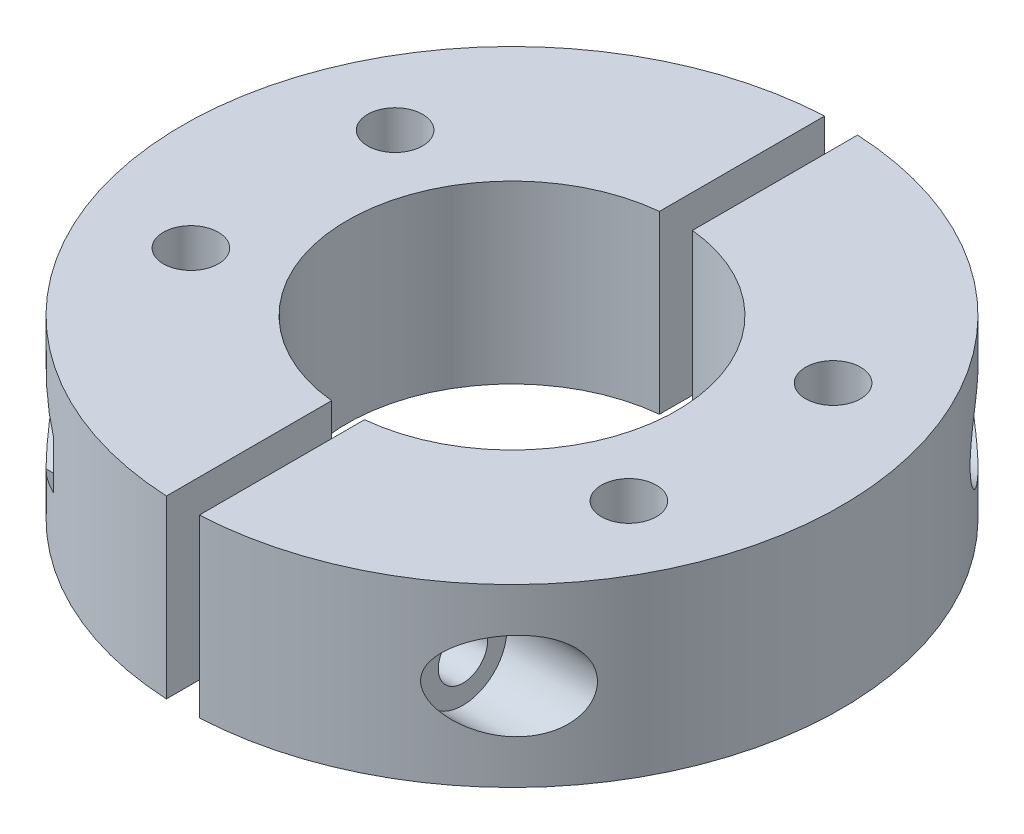
SolidWorks part; units mm, degrees
material "3D printed plastic"
ref_plane "Front Plane" through (0, 0, 0) normal (0, 0, 1) x (1, 0, 0)
ref_plane "Top Plane" through (0, 0, 0) normal (0, 1, 0) x (1, 0, 0)
ref_plane "Right Plane" through (0, 0, 0) normal (1, 0, 0) x (0, 0, -1)
sketch "Sketch1" plane through (0, 0, 0) normal (0, 1, 0) x (1, 0, 0)
  line L0 (-1.5, 29.9625) -> (-1.5, 14.9248)
  line L1 (1.5, -29.9625) -> (1.5, -14.9248)
  line L2 (1.5, 14.9248) -> (1.5, 29.9625)
  line L3 (-1.5, -14.9248) -> (-1.5, -29.9625)
  arc A0 (-1.5, 14.9248) -> (-1.5, -14.9248) centre (0, 0) ccw
  arc A1 (-1.5, 29.9625) -> (-1.5, -29.9625) centre (0, 0) ccw
  arc A2 (1.5, -14.9248) -> (1.5, 14.9248) centre (0, 0) ccw
  arc A3 (1.5, -29.9625) -> (1.5, 29.9625) centre (0, 0) ccw
  dimension "D1" = 30
  dimension "D2" = 60
  dimension "D3" = 3
extrude "Boss-Extrude1" add sketch "Sketch1" along normal blind 16
sketch "Sketch2" plane through (0, 0, 0) normal (1, 0, 0) x (0, 0, -1)
  line L0 (20.9625, 8) -> (29.9625, 8) construction
  line L1 (29.9625, 16) -> (29.9625, 0) construction
  line L2 (-29.9625, 8) -> (-20.9625, 8) construction
  line L3 (-29.9625, 16) -> (-29.9625, 0) construction
  circle A0 centre (-20.9625, 8) radius 2.25
  circle A1 centre (20.9625, 8) radius 2.25
  dimension "D1" = 4.5
  dimension "D2" = 9
extrude "Cut-Extrude1" cut sketch "Sketch2" against normal through all both and the other way through all
sketch "Sketch3" plane through (1.5, 0, 0) normal (-1, 0, 0) x (0, 0, 1)
  circle A0 centre (-20.9625, 8) radius 4
  circle A1 centre (20.9625, 8) radius 4
  dimension "D1" = 8
extrude "Cut-Extrude2" cut sketch "Sketch3" against normal through all from offset 15 offset against normal yes
sketch "Sketch4" plane through (-1.5, 0, 0) normal (1, 0, 0) x (0, 0, -1)
  line L1 (-20.9625, 12.3301) -> (-24.7125, 10.1651)
  line L2 (-24.7125, 10.1651) -> (-24.7125, 5.8349)
  line L3 (-24.7125, 5.8349) -> (-20.9625, 3.6699)
  line L4 (-20.9625, 3.6699) -> (-17.2125, 5.8349)
  line L5 (-17.2125, 5.8349) -> (-17.2125, 10.1651)
  line L6 (-17.2125, 10.1651) -> (-20.9625, 12.3301)
  line L7 (20.9625, 12.3301) -> (17.2125, 10.1651)
  line L8 (17.2125, 10.1651) -> (17.2125, 5.8349)
  line L9 (17.2125, 5.8349) -> (20.9625, 3.6699)
  line L10 (20.9625, 3.6699) -> (24.7125, 5.8349)
  line L11 (24.7125, 5.8349) -> (24.7125, 10.1651)
  line L12 (24.7125, 10.1651) -> (20.9625, 12.3301)
  circle A0 centre (-20.9625, 8) radius 3.75 construction
  circle A1 centre (20.9625, 8) radius 3.75 construction
  dimension "D1" = 7.5
extrude "Cut-Extrude3" cut sketch "Sketch4" against normal through all from offset 12 offset against normal yes
sketch "Sketch5" plane through (0, 16, 0) normal (0, 1, 0) x (1, 0, 0)
  line L0 (-19.9388, 9.2976) -> (-19.9388, -9.2976) construction
  line L1 (-19.9388, -9.2976) -> (0, 0) construction
  line L2 (0, 0) -> (-19.9388, 9.2976) construction
  line L3 (0, 0) -> (0, 8.3239) construction
  circle A0 centre (-19.9388, 9.2976) radius 2.5
  circle A1 centre (-19.9388, -9.2976) radius 2.5
  circle A2 centre (19.9388, -9.2976) radius 2.5
  circle A3 centre (19.9388, 9.2976) radius 2.5
  dimension "D3" = 5
  dimension "D1" = 50
  dimension "D2" = 22
extrude "Cut-Extrude4" cut sketch "Sketch5" against normal through all
